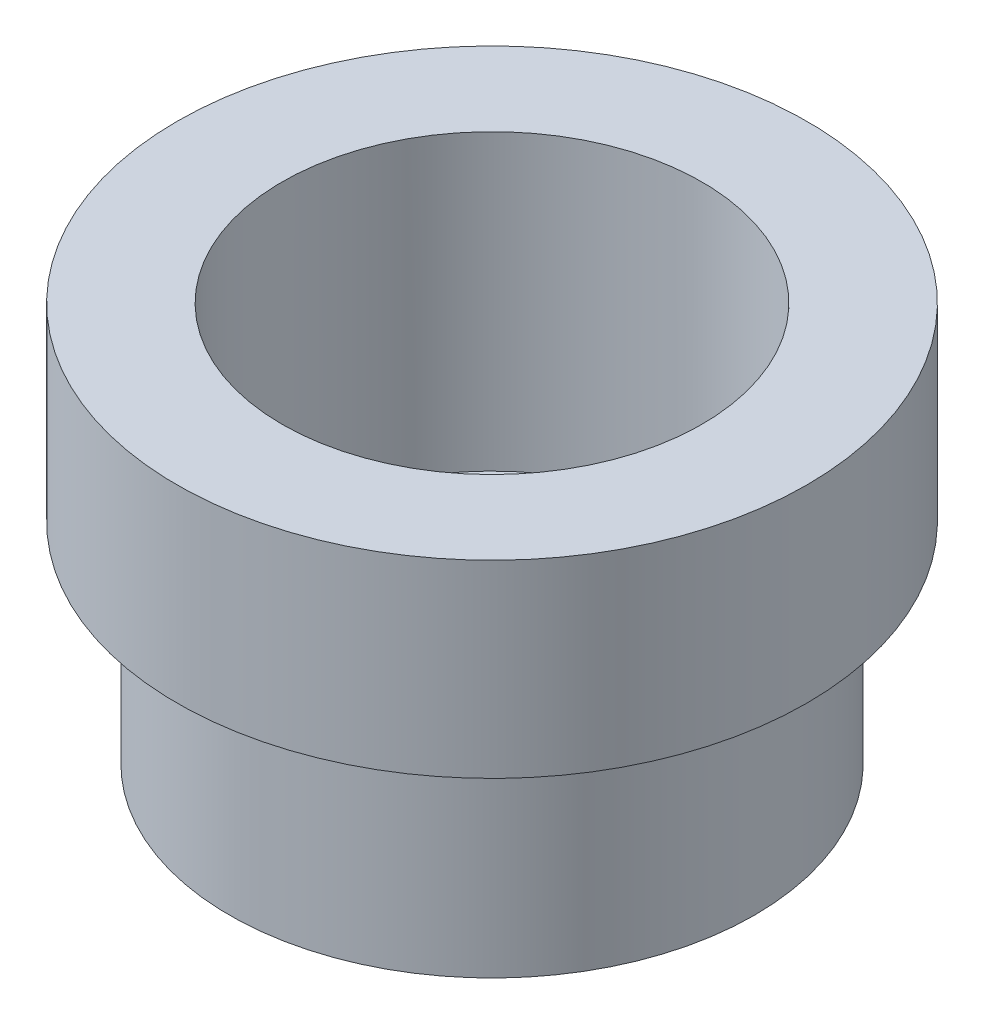
SolidWorks part; units mm, degrees
material "1060 Alloy"
ref_plane "Front" through (0, 0, 0) normal (0, 0, 1) x (1, 0, 0)
ref_plane "Top" through (0, 0, 0) normal (0, 1, 0) x (1, 0, 0)
ref_plane "Right" through (0, 0, 0) normal (1, 0, 0) x (0, 0, -1)
sketch "Sketch1" plane through (0, 0, 0) normal (0, 0, 1) x (1, 0, 0)
  line L0 (0, 0) -> (25, 0)
  line L1 (25, 0) -> (25, 20)
  line L2 (25, 20) -> (30, 20)
  line L3 (30, 20) -> (30, 38)
  line L6 (30, 38) -> (0, 38)
  line L7 (0, 38) -> (0, 0)
  dimension "D1" = 18
  dimension "D2" = 20
  dimension "D3" = 30
  dimension "D4" = 25
revolve "Revolve1" add sketch "Sketch1" angle 360 about L7
sketch "Sketch3" plane through (0, 38, 0) normal (0, 1, 0) x (1, 0, 0)
  circle A0 centre (0, 0) radius 10
  dimension "D1" = 20
extrude "bore through" cut sketch "Sketch3" against normal through all
sketch "Sketch5" plane through (0, 38, 0) normal (0, 1, 0) x (1, 0, 0)
  circle A0 centre (0, 0) radius 20
  dimension "D1" = 40
extrude "center cavity" cut sketch "Sketch5" against normal offset from surface (28 mm away) 10 up to face at (0, 0, 10)
sketch "m4 pattern alignment" plane through (0, 10, 0) normal (0, 1, 0) x (1, 0, 0)
  circle A0 centre (0, 0) radius 15 construction
  circle A1 centre (0, 15) radius 2.15
  point P3 (0, 15)
  point P4 (12.9904, 7.5)
  point P7 (12.9904, -7.5)
  point P8 (0, -15)
  point P9 (-12.9904, -7.5)
  point P10 (-12.9904, 7.5)
  point P11 (0, 0)
  dimension "D1" = 30
  dimension "D3" = 4.3
  dimension "D2" = 6
extrude "Cut-Extrude1" cut sketch "m4 pattern alignment" against normal through all
pattern_circular "CirPattern1" count 6 over 360 about axis through (0, 0, 0) along (0, 1, 0) of "Cut-Extrude1"
sketch "Sketch7" plane through (0, 10, 0) normal (0, 1, 0) x (1, 0, 0)
  circle A0 centre (0, 15) radius 4
extrude "Cut-Extrude2" cut sketch "Sketch7" against normal blind 4
pattern_circular "CirPattern2" count 6 over 360 about axis through (0, 0, 0) along (0, 1, 0) of "Cut-Extrude2"
equation "\"D1\"= \"motor mount plate thickness\""
equation "\"coupler motor shaft hole ID\"= 8mm"
equation "\"coupler OD\"= 17mm"
equation "\"coupler length\"= 25mm"
equation "\"square plate bolt pattern diameter\"= 3.5in"
equation "\"motor mount m4 screw hole diameter\"= 4mm"
equation "\"motor mount m4 head diameter\"= 7.25mm"
equation "\"motor mount m4 head depth\"= 4mm"
equation "\"motor mount plate thickness\"= 8mm + \"motor mount m4 head depth\""
equation "\"motor shaft pride\"= 32mm"
equation "\"motor mount m4 pattern diamater\" = 30mm"
equation "\"motor OD\" = 64mm"
equation "\"square plate bolt bore\" = \"m8 clearance\""
equation "\"square plate bolt head diameter\" = 13.5mm"
equation "\"motor to bearing plate distance\" = \"motor shaft pride\" + 2mm +\"coupler length\"/2"
equation "\"motor mount center bore\"= \"coupler OD\"+ 4mm"
equation "\"motor mount post radius\"= ( 3 * \"square plate bolt bore\" ) / 2"
equation "\"motor shaft diameter\"= 8mm"
equation "\"D1\"= 20mm"
equation "\"z\" = 8\t\t\t\t'number of blades"
equation "\"de\" = 0.43in\t\t\t'entrance eye diameter"
equation "\"de_length\" = 4mm\t\t'entrance eye consistent length"
equation "\"d_exit\" = 0.18in \t\t'throat aka d1"
equation "\"d2\" = 2.1in \t\t\t'outer diameter of the impeller"
equation "\"b2\" = .2in\t\t\t'tip height from disc surface at d2; slightly higher than d_exit"
equation "\"theta\" = 12\t\t\t'angle of blades from inner to outer "
equation "\"ae\" = 3.14*(\"de\"^2)/4\t\t'entrance eye area'"
equation "\"ce\" = 3.14*\"de\"\t\t'entrance eye circumference"
equation "\"av_ratio\" = .325\t\t'ratio of av/ae at N_s of 470, range is .275 to .375, .325 ideal. High ratio means bigger area means smaller blades"
equation "\"av\" = \"ae\"*\"av_ratio\"\t\t'area between just two blades"
equation "\"min blade thickness\" = .15in"
equation "\"diffuser cartridge OD\" =.75in"
equation "\"diffuser flange bolt pattern diameter\" = 1.4in"
equation "\"bearing OD\" = 30mm"
equation "\"bearing ID\"= 10mm"
equation "\"bearing depth\"= 9mm"
equation "\"bearing outer race thickness\"= 1mm"
equation "\"bearing inner race thickness\"= 1mm"
equation "\"bearing bore\" = \"bearing depth\" + 1mm"
equation "\"lower seal OD\" = .917in\t\t'this is https://www.mcmaster.com/#9281k121/=174001b"
equation "\"lower seal ID\"= .375in"
equation "\"lower seal depth\" = .625in + .218in"
equation "\"lower seal bore\" = \"lower seal depth\" + 1mm"
equation "\"upper seal OD\" = 1.125in\t'this is https://www.mcmaster.com/#5154t33/=173zuau, needs to be visually inspected before machining!"
equation "\"upper seal ID\"= 0.625in"
equation "\"upper seal depth\"= .25in\t'aka height; these values need to be confirmed by inspection!! We may want to compress the height."
equation "\"upper seal bore\" = \"upper seal depth\" + 1mm"
equation "\"big o-ring thickness\" = .139in"
equation "\"big o-ring OD\" = 2.734in"
equation "\"big o-ring ID\" = 3.012in"
equation "\"big o-ring groove depth\" = \"big o-ring thickness\"*4/5"
equation "\"impeller upper clearance\"= .5mm"
equation "\"impeller horizontal clearance\"= (\"d2\"*1.15 - \"d2\")/2 \t\t'clearance based on D2-D3 ratio for circular volute, ranges 1.15 to 1.2"
equation "\"impeller bottom clearance\"= .5mm"
equation "\"impeller base thickness\"= 2mm"
equation "\"impeller dowel diameter\" = 2mm"
equation "\"impeller bolt head depth\" = 4mm"
equation "\"impeller bolt stop depth\" = 3mm"
equation "\"impeller shaft bore depth\" = 12mm"
equation "\"impeller shaft bore\" = 8mm"
equation "\"impeller boss depth\" = \"impeller shaft bore depth\"+\"impeller bolt stop depth\"+\"impeller bolt head depth\"-\"impeller base thickness\""
equation "\"impeller boss diameter\" = \"upper seal ID\""
equation "\"impeller dowel length\" = 2mm*2 + \"impeller shaft bore\""
equation "\"square plate bolt head depth\" = 8mm"
equation "\"bearing plate stop ID\" = \"bearing OD\" - 4mm"
equation "\"bearing plate stop depth\" = 3mm"
equation "\"lower seal plate lip depth\" = 2mm"
equation "\"lower seal plate lip ID\" = \"lower seal OD\" - 3mm"
equation "\"lower seal plate thickness\" = \"lower seal plate lip depth\" + \"lower seal bore\""
equation "\"shaft coupler section diameter\" = 8mm"
equation "\"shaft coupler section length\" = \"motor to bearing plate distance\" - \"motor shaft pride\" - 2mm"
equation "\"shaft bearing section diameter\" = \"bearing ID\""
equation "\"shaft bearing section length\" = \"bearing plate stop depth\" + \"bearing depth\""
equation "\"shaft bearing stop diameter\" = \"bearing ID\" + 4mm"
equation "\"shaft bearing stop length\" = 3mm"
equation "\"shaft lower seal section diameter\" = \"lower seal ID\""
equation "\"shaft lower seal section length\" = \"lower seal plate thickness\" + 1mm"
equation "\"shaft impeller section diameter\" = \"impeller shaft bore\""
equation "\"upper seal plate lip ID\" = \"upper seal OD\" - 3mm"
equation "\"upper seal plate riser\" = 6.59mm \t\t'this number needs to be read from the housing file"
equation "\"upper seal plate pressure hole diameter\" = .125in\t'this is 1/8 drill "
equation "\"upper seal plate pressure tap diameter\" = .328125in \t'this is 21/64 drill for a 1/8 ANPT tap"
equation "\"upper seal plate pressure tap grip\" = 5mm\t\t'this is the area around the tap so it doesn't crack"
equation "\"upper seal plate pressure tap depth\" = 12mm"
equation "\"impeller cavity diameter\"= 2 * \"impeller horizontal clearance\" + \"d2\" \t\t\t\t\t\t\t\t\t'called D3 analytically"
equation "\"impeller cavity outer height\"= \"impeller bottom clearance\" + \"impeller upper clearance\" + \"impeller base thickness\" + \"b2\" \t\t'this is height at impeller diameter d2, not at d3"
equation "\"impeller housing diameter\" = 4.5in"
equation "\"impeller housing bolt count\" = 8"
equation "\"impeller housing bolt pattern diameter\" = 3.5in"
equation "\"impeller housing threaded inlet diameter\" = 0.71875in \t'this is the 23/32 drill size for 1/2 NPT fitting https://www.mcmaster.com/#50715k269/=176pljy"
equation "\"impeller housing threaded inlet depth\"= .6in"
equation "\"impeller housing exit threaded diameter\"= 0.515625in \t\t'this is the 33/64 drill size for 9/16-18 fitting, expecting swagelok SS-8FK0-1-6STH fitting"
equation "\"impeller housing exit threaded depth\"= 10mm"
equation "\"impeller housing diffuser conical angle\"=10"
equation "\"impeller housing diffuser tangent angle\"=5"
equation "\"impeller housing diffuser final diameter\" = .38in\t\t'aka d2'"
equation "\"impeller housing outlet grip\" = 5mm"
equation "\"end mill size\" = 0.375in\t'for 3/8 endmill"
equation "\"m4 clearance\" = 0.171875in \t'this is 11/64 bit for 4.36mm"
equation "\"m4 tap\" = 0.125in\t\t'this is 1/8 bit for 3.17mm"
equation "\"m4 head bore diameter\" = 7.5mm"
equation "\"m4 head bore depth\" = 5mm\t'actual is ~4mm"
equation "\"m6 clearance\" = 0.234375in\t'this is 15/64 bit = 5.95mm, could use 6mm bit, B bit for 6.04mm or 1/4 bit for 6.35mm"
equation "\"m6 tap\" = 5mm\t\t\t'5mm is appropriate, could use 13/64 or #5,6,7"
equation "\"m6 head bore diameter\" = 11mm\t\t"
equation "\"m6 head bore depth\" = 7mm\t'actual is 6mm"
equation "\"m8 clearance\" = 0.3125in\t'this is 5/16in for 7.93mm, could use 8mm, O,P, or 21/64"
equation "\"m8 tap\" = 0.265625in\t\t'this is 17/64 for 6.746875mm"
equation "\"m8 head bore diameter\" = 14mm"
equation "\"m8 head bore depth\" = 9mm\t'actual is 8mm"
